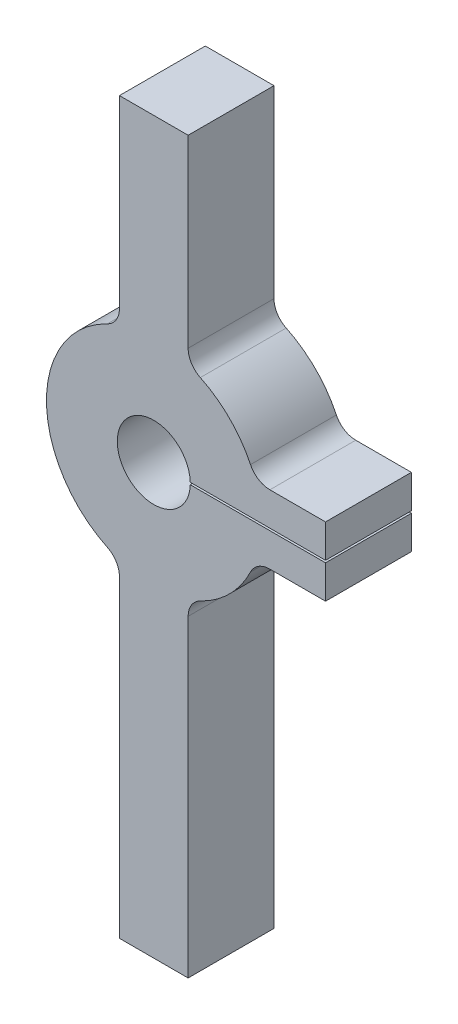
SolidWorks part; units mm, degrees
ref_plane "Front Plane" through (0, 0, 0) normal (0, 0, 1) x (1, 0, 0)
ref_plane "Top Plane" through (0, 0, 0) normal (0, 1, 0) x (1, 0, 0)
ref_plane "Right Plane" through (0, 0, 0) normal (1, 0, 0) x (0, 0, -1)
sketch "Sketch1" plane through (0, 0, 0) normal (0, 0, 1) x (1, 0, 0)
  circle A0 centre (0, 0) radius 8.5
  circle A1 centre (0, 0) radius 25
  dimension "D1" = 17
  dimension "D2" = 50
extrude "Boss-Extrude1" add sketch "Sketch1" along normal mid plane 20
sketch "Sketch2" plane through (0, 0, 0) normal (0, 0, 1) x (1, 0, 0)
  line L0 (0, 0) -> (0, 40.1669) construction
  line L1 (-8, 70) -> (8, 70)
  line L2 (8, 70) -> (8, 23.6854)
  line L3 (8, 23.6854) -> (-8, 23.6854)
  line L4 (-8, 70) -> (-8, 23.6854)
  circle A0 centre (0, 0) radius 25 construction
  point P10 (0, 23.6854)
  point P11 (0, 70)
  dimension "D1" = 16
  dimension "D2" = 70
extrude "Boss-Extrude2" add sketch "Sketch2" along normal mid plane 20
sketch "Sketch3" plane through (0, 0, 0) normal (0, 0, 1) x (1, 0, 0)
  line L0 (0, 0) -> (0, -28.6568) construction
  line L1 (-8, -100) -> (8, -100)
  line L2 (8, -100) -> (8, -23.6854)
  line L3 (8, -23.6854) -> (-8, -23.6854)
  line L4 (-8, -100) -> (-8, -23.6854)
  arc A0 (-8, 23.6854) -> (8, 23.6854) centre (0, 0) ccw construction
  point P11 (0, -23.6854)
  point P12 (0, -100)
  dimension "D1" = 16
  dimension "D2" = 100
extrude "Boss-Extrude3" add sketch "Sketch3" along normal mid plane 20
sketch "Sketch4" plane through (0, 0, 0) normal (0, 0, 1) x (1, 0, 0)
  line L0 (0, 0) -> (85.7397, 0) construction
  line L1 (40, -8) -> (40, 8)
  line L2 (40, 8) -> (23.6854, 8)
  line L3 (23.6854, 8) -> (23.6854, -8)
  line L4 (40, -8) -> (23.6854, -8)
  arc A0 (8, -23.6854) -> (8, 23.6854) centre (0, 0) ccw construction
  point P11 (40, 0)
  point P12 (23.6854, 0)
  dimension "D1" = 16
  dimension "D2" = 40
extrude "Boss-Extrude4" add sketch "Sketch4" along normal mid plane 20
sketch "Sketch5" plane through (0, 0, 0) normal (0, 0, 1) x (1, 0, 0)
  line L0 (0, 0) -> (67.4641, 0) construction
  line L1 (2, -0.25) -> (2, 0.25)
  line L2 (2, 0.25) -> (50, 0.25)
  line L3 (50, 0.25) -> (50, -0.25)
  line L4 (2, -0.25) -> (50, -0.25)
  point P8 (50, 0)
  point P9 (2, 0)
  dimension "D1" = 0.5
  dimension "D2" = 50
  dimension "D3" = 2
extrude "Cut-Extrude1" cut sketch "Sketch5" against normal through all both and the other way through all
fillet "Fillet1" radius 5 6 edges at (-8, -23.6854, 0) (-8, 23.6854, 0) (8, -23.6854, 0) (23.6854, 8, 0) (8, 23.6854, 0) (23.6854, -8, 0)
sketch "Sketch7" plane through (0, 0, 0) normal (1, 0, 0) x (0, 0, -1)
  line L0 (0, 0) -> (12.2593, 0) construction
  line L1 (7, 8.5) -> (7, 14)
  line L2 (10, 8.5) -> (-10, 8.5) construction
  line L3 (7, 14) -> (10, 14)
  line L4 (10, 10.8333) -> (10, 22.5308) construction
  line L5 (10, 14) -> (10, 8.5)
  line L6 (10, 8) -> (10, 10.8333) construction
  line L7 (10, 8.5) -> (7, 8.5)
  dimension "D1" = 3
  dimension "D2" = 14
revolve "Cut-Revolve1" cut sketch "Sketch7" angle 360 about L0
